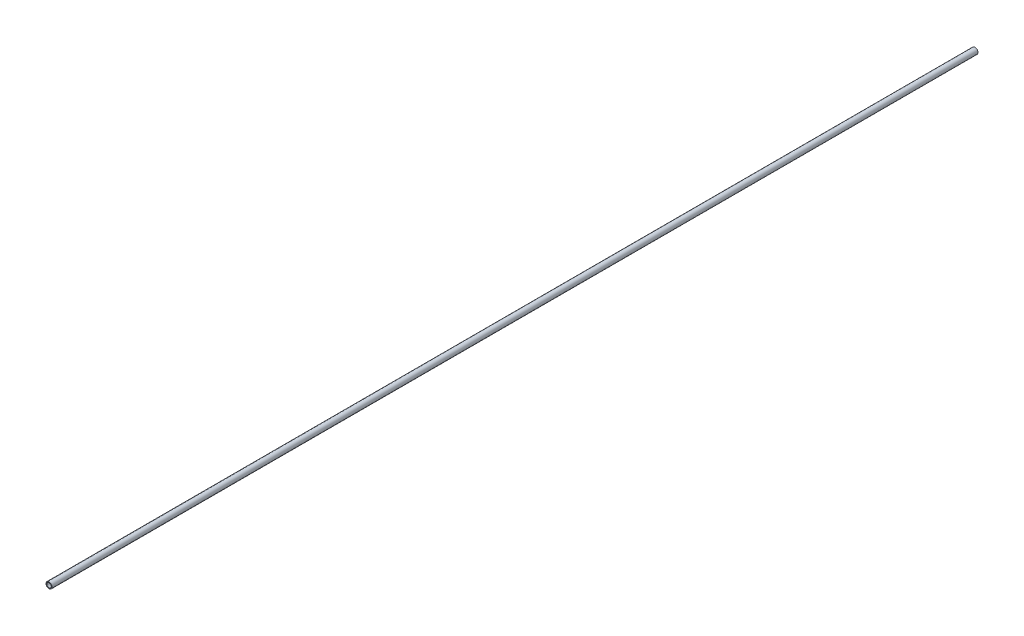
SolidWorks part; units mm, degrees
material "Thornel Mat VMA"
ref_plane "前视基准面" through (0, 0, 0) normal (0, 0, 1) x (1, 0, 0)
ref_plane "上视基准面" through (0, 0, 0) normal (0, 1, 0) x (1, 0, 0)
ref_plane "右视基准面" through (0, 0, 0) normal (1, 0, 0) x (0, 0, -1)
other "Configuration Table"
sketch "草图1" plane through (0, 0, 0) normal (0, 0, 1) x (1, 0, 0)
  circle A0 centre (0, 0) radius 4
  circle A1 centre (0, 0) radius 3
  dimension "D1" = 8
  dimension "D2" = 6
extrude "凸台-拉伸1" add sketch "草图1" along normal blind 1230
